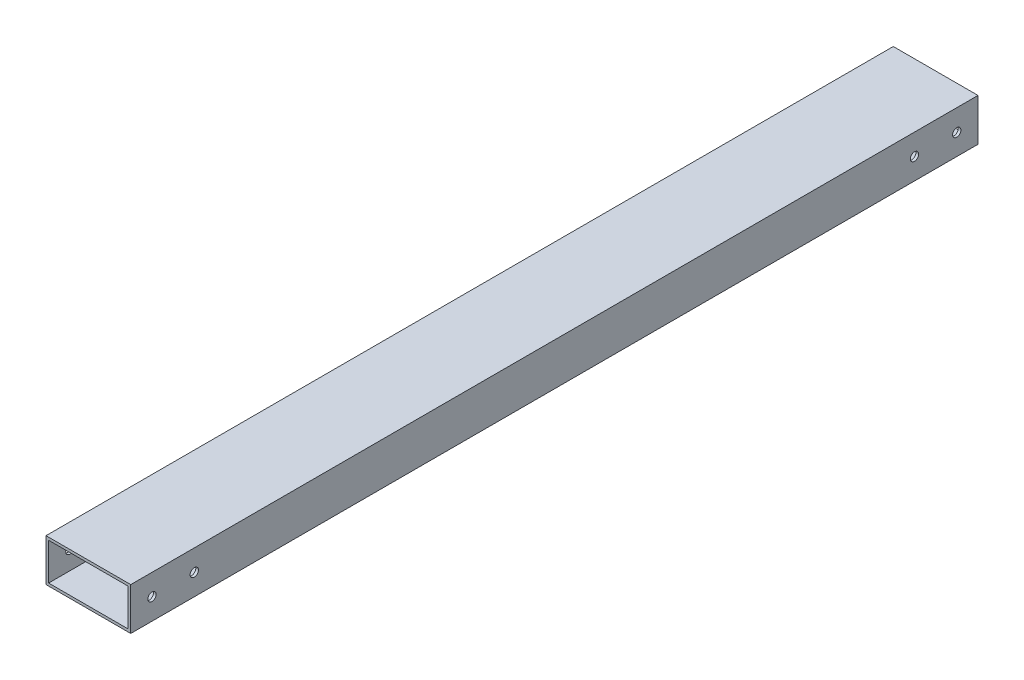
SolidWorks part; units mm, degrees
ref_plane "Front Plane" through (0, 0, 0) normal (0, 0, 1) x (1, 0, 0)
ref_plane "Top Plane" through (0, 0, 0) normal (0, 1, 0) x (1, 0, 0)
ref_plane "Right Plane" through (0, 0, 0) normal (1, 0, 0) x (0, 0, -1)
sketch "Sketch1" plane through (0, 0, 0) normal (0, 0, 1) x (1, 0, 0)
  line L0 (-23.8125, 11.1125) -> (23.8125, 11.1125)
  line L2 (-25.4, 12.7) -> (25.4, 12.7)
  line L3 (-25.4, 12.7) -> (-25.4, -12.7)
  line L4 (-25.4, -12.7) -> (25.4, -12.7)
  line L5 (25.4, 12.7) -> (25.4, -12.7)
  line L10 (23.8125, 11.1125) -> (23.8125, -11.1125)
  line L11 (-23.8125, -11.1125) -> (23.8125, -11.1125)
  line L12 (-23.8125, 11.1125) -> (-23.8125, -11.1125)
  point P12 (0, 12.7)
  point P14 (25.4, 0)
  dimension "Wall Thickness" = 1.5875
  dimension "Outside Width" = 50.8
  dimension "Outside Height" = 25.4
  dimension "Inside Height" = 22.225
  dimension "Inside Width" = 47.625
sketch "Sketch2" plane through (0, 0, 0) normal (1, 0, 0) x (0, 0, -1)
  line L0 (254, 0) -> (-254, 0)
  point P4 (0, 0)
  point P7 (-254, 0)
  point P10 (254, 0)
  dimension "Length" = 508
sketch "Sketch3" plane through (0, 0, 0) normal (0, 0, 1) x (1, 0, 0)
  line L21 (25.4, 12.7) -> (-25.4, 12.7)
  line L22 (25.4, -12.7) -> (25.4, 12.7)
  line L23 (-25.4, -12.7) -> (25.4, -12.7)
  line L24 (-25.4, 12.7) -> (-25.4, -12.7)
  line L25 (25.4, 12.7) -> (-25.4, 12.7)
  line L26 (25.4, -12.7) -> (25.4, 12.7)
  line L27 (-25.4, -12.7) -> (25.4, -12.7)
  line L28 (-25.4, 12.7) -> (-25.4, -12.7)
  line L29 (23.8125, 11.1125) -> (-23.8125, 11.1125)
  line L30 (23.8125, -11.1125) -> (23.8125, 11.1125)
  line L31 (-23.8125, -11.1125) -> (23.8125, -11.1125)
  line L32 (-23.8125, 11.1125) -> (-23.8125, -11.1125)
  line L33 (23.8125, 11.1125) -> (-23.8125, 11.1125)
  line L34 (23.8125, -11.1125) -> (23.8125, 11.1125)
  line L35 (-23.8125, -11.1125) -> (23.8125, -11.1125)
  line L36 (-23.8125, 11.1125) -> (-23.8125, -11.1125)
  dimension "D1" = 0
  dimension "D2" = 0
extrude "Boss-Extrude1" add sketch "Sketch3" along normal up to vertex (254 mm away) and the other way up to vertex (254 mm away) up to point (0, 0, 254) other way up to point (0, 0, -254)
sketch "Drawing Reference" plane through (0, 0, 0) normal (1, 0, 0) x (0, 0, -1)
  line L0 (-254, 0) -> (254, 0) construction
  line L1 (0, -12.7) -> (0, 12.7) construction
  line L2 (-254, -12.7) -> (254, -12.7) construction
  line L5 (-254, 12.7) -> (254, 12.7) construction
  point P7 (-217.424, 0)
  point P8 (217.424, 0)
  dimension "D1" = 36.576
hole_wizard "#10 Clearance Hole1" positions "Sketch4" profile "Sketch5" hole size "#10" standard "ANSI Inch" end condition through all
sketch "Sketch4" plane through (25.4, 0, 0) normal (1, 0, 0) x (0, 0, -1)
  point P3 (-215.9, 0)
  point P12 (-241.2618, 0)
  point P18 (215.9, 0)
  point P23 (241.2618, -0.1635)
sketch "Sketch5" plane through (25.4, 0, 215.9) normal (0, 1, 0) x (0, 0, -1)
  line L0 (0, 0) -> (0, 50.8)
  line L1 (0, 50.8) -> (2.4892, 50.8)
  line L2 (2.4892, 50.8) -> (2.4892, 0)
  line L5 (2.4892, 0) -> (0, 0)
  line L11 (0, -6.35) -> (0, 107.95) construction
  dimension "Thru Hole Dia." = 4.9784
  dimension "Thru Hole Depth" = 50.8
equation "\"D1@Drawing Reference\"=\"Outside Width@Sketch1\" * 0.72"
